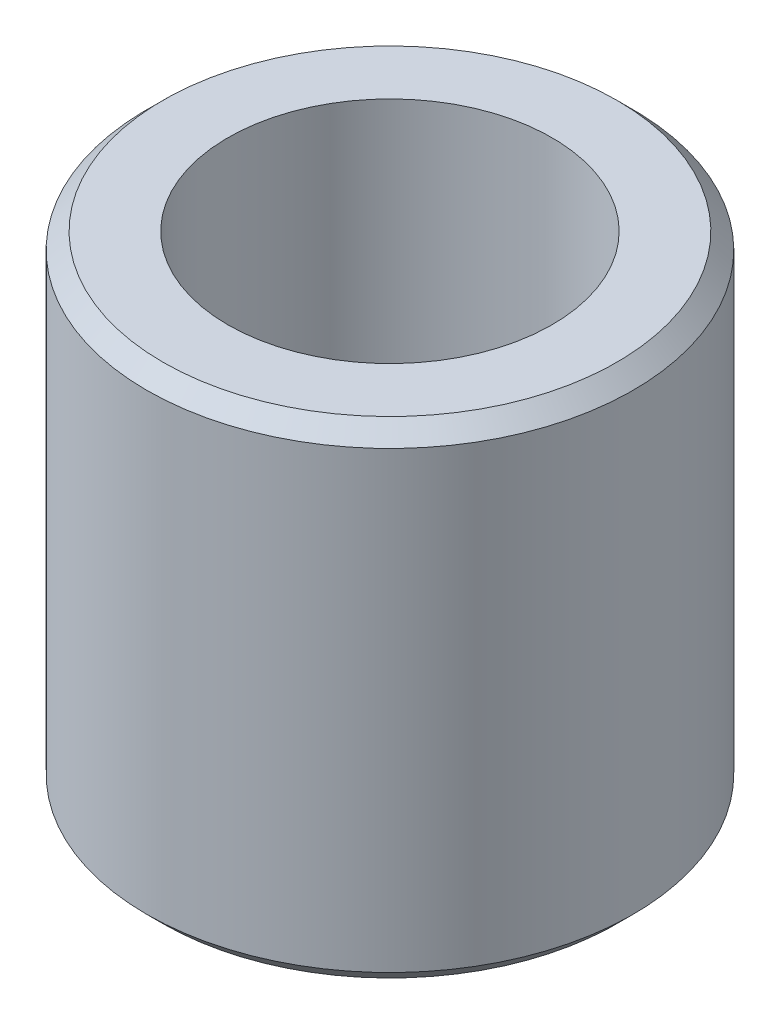
SolidWorks part; units mm, degrees
ref_plane "Front Plane" through (0, 0, 0) normal (0, 0, 1) x (1, 0, 0)
ref_plane "Top Plane" through (0, 0, 0) normal (0, 1, 0) x (1, 0, 0)
ref_plane "Right Plane" through (0, 0, 0) normal (1, 0, 0) x (0, 0, -1)
sketch "Sketch3" plane through (0, 0, 0) normal (0, 1, 0) x (1, 0, 0)
  circle A0 centre (0, 0) radius 15
  circle A1 centre (0, 0) radius 10
  dimension "D1" = 20
  dimension "D2" = 30
extrude "Boss-Extrude1" add sketch "Sketch3" along normal mid plane 30
chamfer "Chamfer1" distance 1 angle 45 2 edges at (0, -15, 15) (0, 15, 15)
